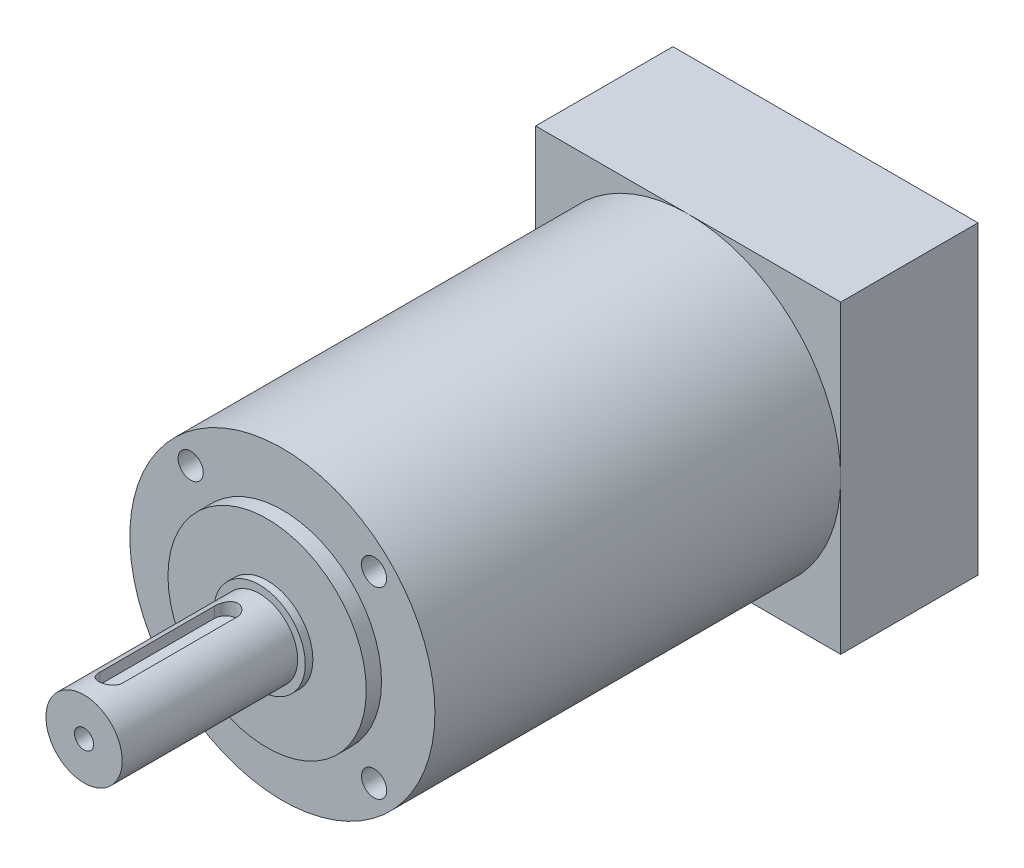
SolidWorks part; units mm, degrees
ref_plane "Front" through (0, 0, 0) normal (0, 0, 1) x (1, 0, 0)
ref_plane "Top" through (0, 0, 0) normal (0, 1, 0) x (1, 0, 0)
ref_plane "Right" through (0, 0, 0) normal (1, 0, 0) x (0, 0, -1)
sketch "Эскиз1" plane through (0, 0, 0) normal (0, 0, 1) x (1, 0, 0)
  line L1 (0, 0) -> (40, 0)
  line L2 (0, 0) -> (0, 40)
  line L3 (0, 40) -> (40, 40)
  line L4 (40, 0) -> (40, 40)
  dimension "D1" = 40
  dimension "D2" = 40
extrude "Бобышка-Вытянуть1" add sketch "Эскиз1" along normal blind 18
sketch "Эскиз2" plane through (0, 0, 18) normal (0, 0, 1) x (1, 0, 0)
  line L1 (0, 0) -> (40, 0) construction
  line L2 (40, 0) -> (40, 40) construction
  circle A0 centre (20, 20) radius 20
  dimension "D1" = 40
extrude "Бобышка-Вытянуть2" add sketch "Эскиз2" along normal blind 53.2
sketch "Эскиз3" plane through (0, 0, 71.2) normal (0, 0, 1) x (1, 0, 0)
  circle A0 centre (20, 20) radius 13
  arc A1 (40, 20) -> (20, 40) centre (20, 20) ccw construction
  dimension "D1" = 26
extrude "Бобышка-Вытянуть3" add sketch "Эскиз3" along normal blind 2
sketch "Эскиз4" plane through (0, 0, 73.2) normal (0, 0, 1) x (1, 0, 0)
  circle A0 centre (20, 20) radius 6
  circle A1 centre (20, 20) radius 13 construction
  dimension "D1" = 12
extrude "Бобышка-Вытянуть4" add sketch "Эскиз4" along normal blind 1
sketch "Эскиз5" plane through (0, 0, 74.2) normal (0, 0, 1) x (1, 0, 0)
  circle A0 centre (20, 20) radius 5
  circle A1 centre (20, 20) radius 6 construction
  dimension "D1" = 10
extrude "Бобышка-Вытянуть5" add sketch "Эскиз5" along normal blind 23 contours A0
ref_plane "Плоскость3" through (0, 25, 0) normal (0, -1, 0) x (-1, 0, 0)
sketch "Эскиз9" plane through (0, 25, 0) normal (0, -1, 0) x (-1, 0, 0)
  line L0 (-19.5685, -93.2) -> (-19.5685, -78.2) construction
  line L1 (-21.0685, -93.2) -> (-21.0685, -78.2)
  line L2 (-18.0685, -93.2) -> (-18.0685, -78.2)
  line L3 (-25, -97.2) -> (-15, -97.2) construction
  arc A0 (-21.0685, -93.2) -> (-18.0685, -93.2) centre (-19.5685, -93.2) ccw
  arc A1 (-18.0685, -78.2) -> (-21.0685, -78.2) centre (-19.5685, -78.2) ccw
  point P2 (-19.5685, -85.7)
  dimension "D2" = 1.5
  dimension "D1" = 15
  dimension "D3" = 4
extrude "Вырез-Вытянуть1" cut sketch "Эскиз9" along normal blind 1.8
hole_wizard "Отверстие обработанное метчиком M31" positions "Эскиз11" profile "Эскиз10" tap size "M3" standard "DIN"
sketch "Эскиз11" plane through (0, 0, 97.2) normal (0, 0, 1) x (1, 0, 0)
  circle A0 centre (20, 20) radius 6 construction
  point P0 (20, 20)
sketch "Эскиз10" plane through (20, 20, 97.2) normal (1, 0, 0) x (0, -1, 0)
  line L0 (0, 0) -> (0, 15.7511)
  line L1 (0, 15.7511) -> (1.25, 15)
  line L2 (1.25, 15) -> (1.25, 0)
  line L5 (1.25, 0) -> (0, 0)
  line L10 (0, 15.7511) -> (-1.25, 15) construction
  line L11 (0, -6.35) -> (0, 107.95) construction
  dimension "Диаметр сверла" = 2.5
  dimension "Глубина сверла" = 15
  dimension "Угол заточки сверла" = 118
cosmetic thread "Отверстие резьбы1" parameters "D1"=10, "D2"=3
sketch "Эскиз12" plane through (0, 0, 71.2) normal (0, 0, 1) x (1, 0, 0)
  line L0 (7.9792, 32.0208) -> (20, 20)
  line L1 (20, 20) -> (3, 20)
  circle A0 centre (20, 20) radius 17
  point P3 (7.9792, 32.0208)
  dimension "D1" = 34
  dimension "D2" = 45
hole_wizard "Отверстие обработанное метчиком M41" positions "Эскиз13" profile "Эскиз14" tap size "M4" standard "DIN"
sketch "Эскиз13" plane through (0, 0, 71.2) normal (0, 0, 1) x (1, 0, 0)
  point P0 (7.9792, 32.0208)
sketch "Эскиз14" plane through (7.9792, 32.0208, 71.2) normal (1, 0, 0) x (0, -1, 0)
  line L0 (0, 0) -> (0, 7.9914)
  line L1 (0, 7.9914) -> (1.65, 7)
  line L2 (1.65, 7) -> (1.65, 0)
  line L5 (1.65, 0) -> (0, 0)
  line L10 (0, 7.9914) -> (-1.65, 7) construction
  line L11 (0, -6.35) -> (0, 107.95) construction
  dimension "Диаметр сверла" = 3.3
  dimension "Глубина сверла" = 7
  dimension "Угол заточки сверла" = 118
cosmetic thread "Отверстие резьбы2" parameters "D1"=7, "D2"=4
pattern_circular "Круговой массив1" count 4 over 360 about axis through (20, 20, 0) along (0, 0, 1) of "Отверстие обработанное метчиком M41"
cosmetic thread "Отверстие резьбы3" parameters "D1"=7, "D2"=4
cosmetic thread "Отверстие резьбы4" parameters "D1"=7, "D2"=4
cosmetic thread "Отверстие резьбы5" parameters "D1"=7, "D2"=4
